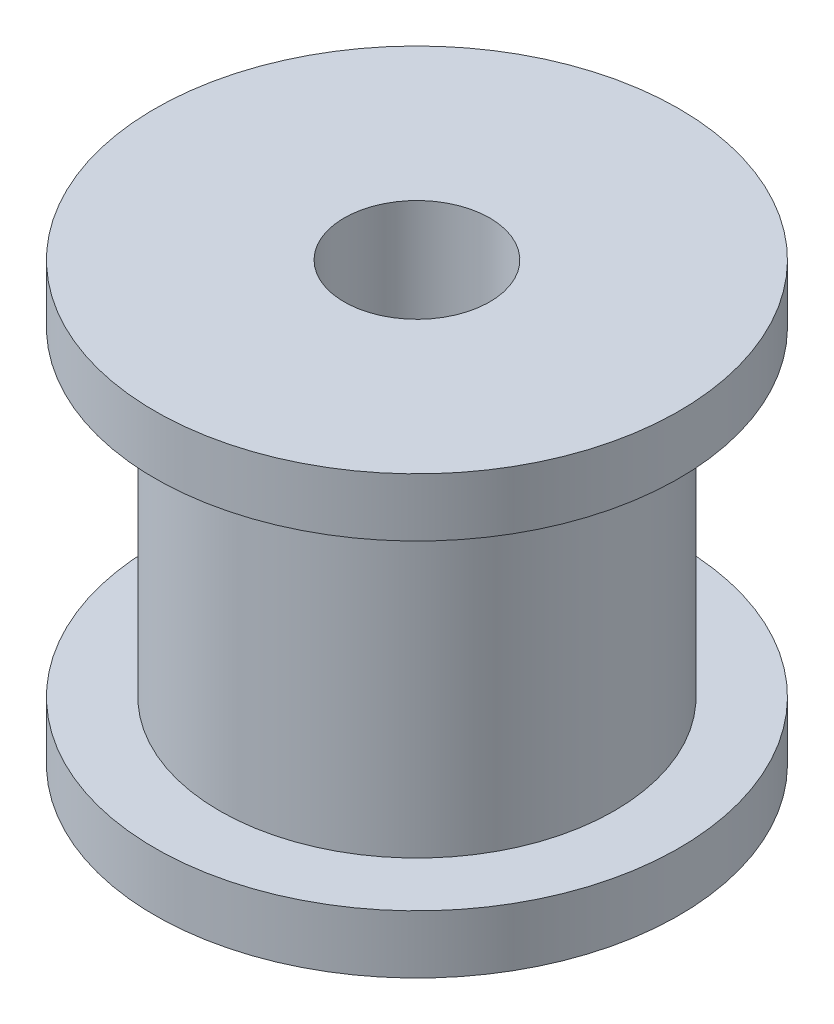
SolidWorks part; units mm, degrees
ref_plane "前视基准面" through (0, 0, 0) normal (0, 0, 1) x (1, 0, 0)
ref_plane "上视基准面" through (0, 0, 0) normal (0, 1, 0) x (1, 0, 0)
ref_plane "右视基准面" through (0, 0, 0) normal (1, 0, 0) x (0, 0, -1)
other "Configuration Table"
sketch "草图1" plane through (0, 0, 0) normal (0, 0, 1) x (1, 0, 0)
  line L0 (0, 0) -> (0, 31456.903) construction
  line L1 (2.5, 7.5) -> (9, 7.5)
  line L2 (9, 7.5) -> (9, 5.5)
  line L3 (9, 5.5) -> (6.78, 5.5)
  line L4 (6.78, 5.5) -> (6.78, -5.5)
  line L5 (2.5, 7.5) -> (2.5, -7.5)
  line L6 (0, 0) -> (31456.903, 0) construction
  line L7 (9, -5.5) -> (6.78, -5.5)
  line L8 (9, -7.5) -> (9, -5.5)
  line L9 (2.5, -7.5) -> (9, -7.5)
  point P11 (2.5, 0)
  point P12 (6.78, 0)
  dimension "D1" = 2.5
  dimension "D2" = 9
  dimension "D3" = 11
  dimension "D4" = 15
  dimension "D5" = 6.78
revolve "旋转1" add sketch "草图1" angle 360 about L0
